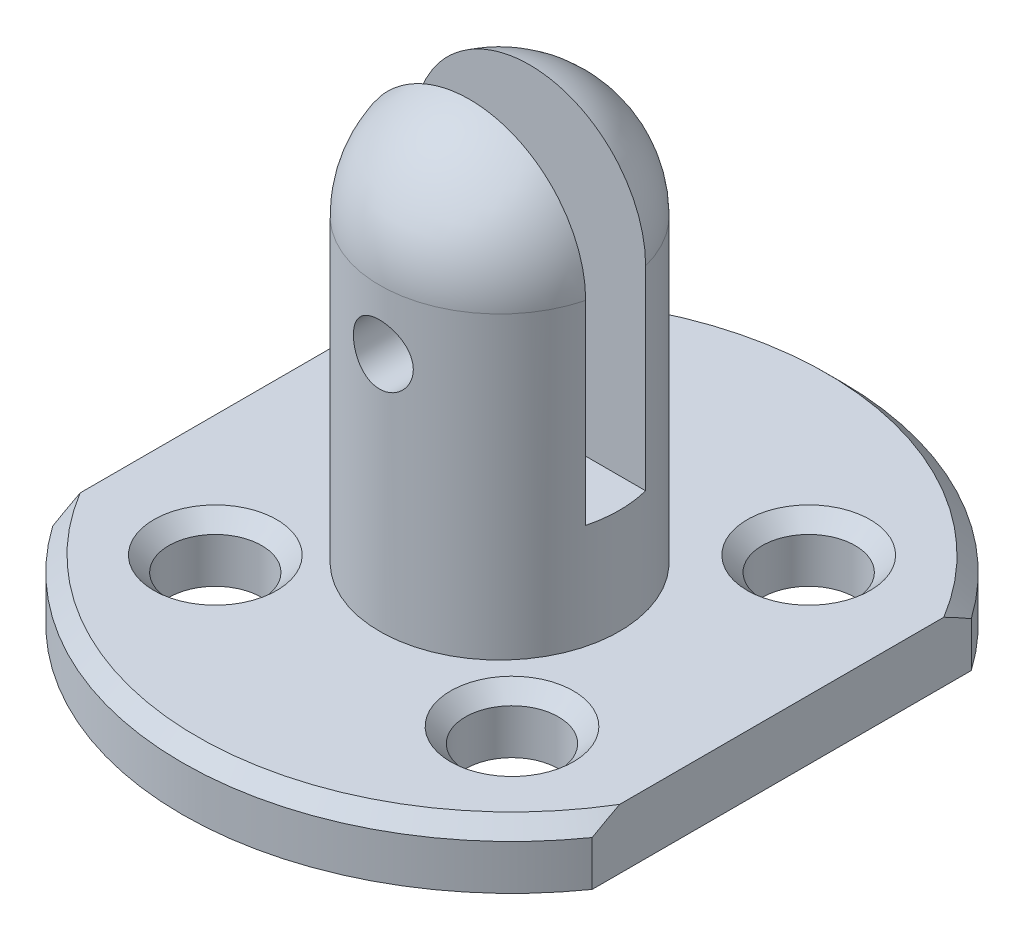
SolidWorks part; units mm, degrees
ref_plane "Front Plane" through (0, 0, 0) normal (0, 0, 1) x (1, 0, 0)
ref_plane "Top Plane" through (0, 0, 0) normal (0, 1, 0) x (1, 0, 0)
ref_plane "Right Plane" through (0, 0, 0) normal (1, 0, 0) x (0, 0, -1)
sketch "Sketch2" plane through (0, 0, 0) normal (0, 1, 0) x (1, 0, 0)
  line L2 (-3.6953, -5.9104) -> (-3.6953, 6.7387)
  line L4 (14.3047, -5.9104) -> (14.3047, 6.7387)
  line L5 (-3.6953, -20.993) -> (14.3047, 21.8212) construction
  line L6 (-3.6953, 21.8212) -> (14.3047, -20.993) construction
  arc A0 (-3.6953, -5.9104) -> (14.3047, -5.9104) centre (5.3047, 0.4141) ccw
  arc A1 (14.3047, 6.7387) -> (-3.6953, 6.7387) centre (5.3047, 0.4141) ccw
  dimension "D1" = 22
  dimension "D2" = 18
extrude "Boss-Extrude1" add sketch "Sketch2" along normal blind 2
sketch "Sketch3" plane through (0, 2, 0) normal (0, 1, 0) x (1, 0, 0)
  line L0 (5.3047, 0.4141) -> (5.3047, 7.4141) construction
  line L1 (5.3047, 7.4141) -> (5.3047, 0.4141) construction
  line L2 (5.3047, 0.4141) -> (10.2545, 5.3639) construction
  circle A0 centre (5.3047, 0.4141) radius 11 construction
  circle A1 centre (5.3047, 0.4141) radius 7 construction
  circle A2 centre (10.2545, 5.3639) radius 1.55
  circle A3 centre (10.2545, -4.5356) radius 1.55
  circle A4 centre (0.355, -4.5356) radius 1.55
  circle A5 centre (0.355, 5.3639) radius 1.55
  point P15 (5.3047, 0.4141)
  dimension "D1" = 14
  dimension "D3" = 3.1
  dimension "D2" = 45
  dimension "D4" = 4
extrude "Cut-Extrude1" cut sketch "Sketch3" against normal through all
chamfer "Chamfer1" distance 0.5 angle 45 6 edges at (10.2545, 2, 6.0856) (0.355, 2, -3.8139) (5.3047, 2, 10.5859) (0.355, 2, 6.0856) (10.2545, 2, -3.8139) (5.3047, 2, -11.4141)
sketch "Sketch4" plane through (0, 0, 0) normal (0, 0, 1) x (1, 0, 0)
  line L0 (5.3047, 16) -> (5.3047, 2)
  line L1 (14.3047, 2) -> (-3.6953, 2) construction
  line L2 (9.3047, 2) -> (9.3047, 12)
  line L3 (9.3047, 2) -> (5.3047, 2)
  arc A1 (9.3047, 12) -> (5.3047, 16) centre (5.3047, 12) ccw
  dimension "D3" = 10
  dimension "D1" = 14
  dimension "D2" = 4
revolve "Revolve2" add sketch "Sketch4" angle 360 about L0
sketch "Sketch9" plane through (0, 0, 0) normal (0, -1, 0) x (1, 0, 0)
  line L0 (5.3047, -0.4141) -> (-5.6953, -0.4141) construction
  line L1 (-5.6953, -0.4141) -> (16.3047, -0.4141) construction
  line L2 (16.3047, -0.4141) -> (18.4848, -14.3838) construction
  circle A0 centre (5.3047, -0.4141) radius 11
sketch "Sketch11" plane through (0, 0, 0) normal (0, -1, 0) x (1, 0, 0)
  line L0 (5.3047, -0.4141) -> (-5.6953, -0.4141) construction
  line L1 (0, -1.1) -> (0, 1.1) construction
  line L2 (5.3047, -0.4141) -> (0, -0.4141)
  point P0 (0, -0.4141)
ref_plane "Plane1" through (5.3, 0, 0) normal (1, 0, 0) x (0, 0, -1)
sketch "Sketch12" plane through (5.3, 0, 0) normal (1, 0, 0) x (0, 0, -1)
  line L0 (-4, 12) -> (4, 12) construction
  line L1 (-1, 18.5) -> (1, 18.5)
  line L2 (-1, 18.5) -> (-1, 5.5)
  line L3 (-1, 5.5) -> (1, 5.5)
  line L4 (1, 18.5) -> (1, 5.5)
  line L5 (-1, 18.5) -> (1, 5.5) construction
  line L6 (-1, 5.5) -> (1, 18.5) construction
  line L7 (-4.9942, 2) -> (5.8225, 2) construction
  point P0 (0, 12)
  dimension "D1" = 2
  dimension "D2" = 3.5
extrude "Cut-Extrude2" cut sketch "Sketch12" against normal mid plane 16
sketch "Sketch13" plane through (0, 0, 0) normal (0, 0, 1) x (1, 0, 0)
  line L0 (5.3, -9.2801) -> (5.3, 9.2801) construction
  line L1 (14.3047, 2) -> (-3.6953, 2) construction
  circle A0 centre (5.3, 10) radius 1
  dimension "D1" = 2
  dimension "D2" = 8
extrude "Cut-Extrude3" cut sketch "Sketch13" against normal mid plane 16
sketch "Sketch14" plane through (0, 0, 0) normal (0, -1, 0) x (1, 0, 0)
  circle A0 centre (5.3047, -0.4141) radius 3
  dimension "D1" = 6
extrude "Boss-Extrude2" add sketch "Sketch14" along normal blind 1
